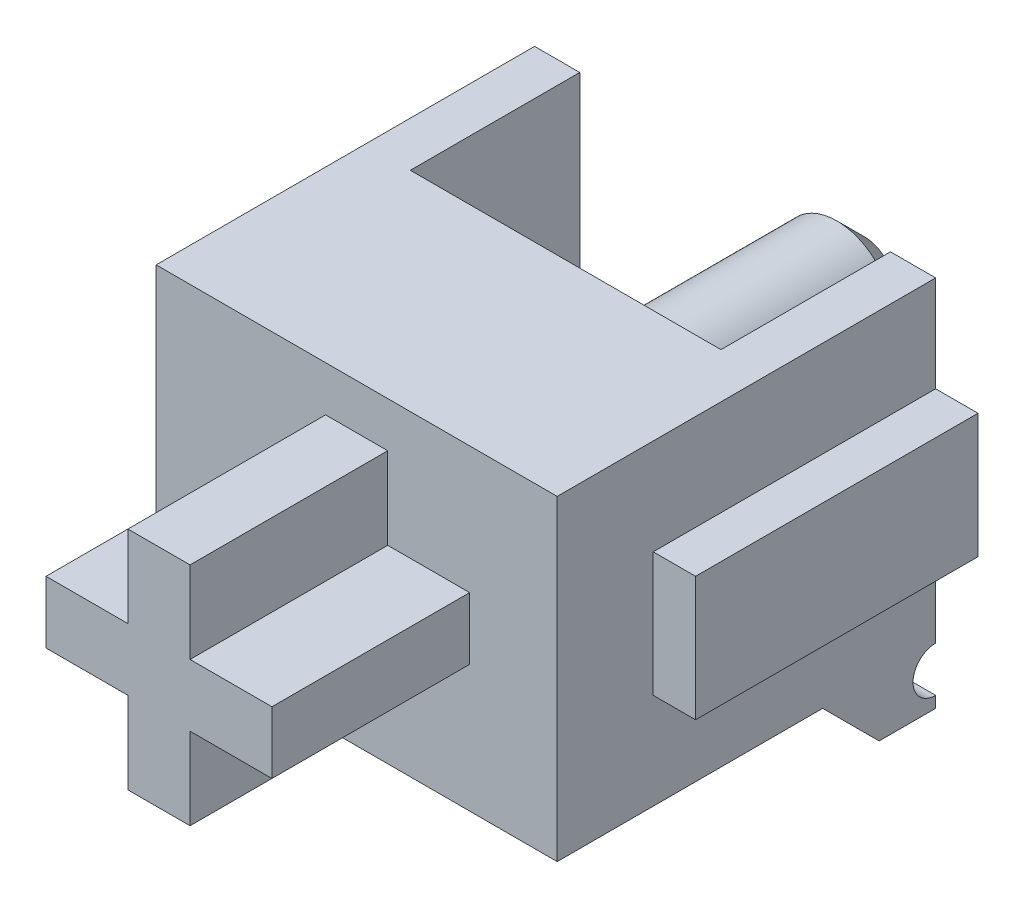
SolidWorks part; units mm, degrees
ref_plane "Front Plane" through (0, 0, 0) normal (0, 0, 1) x (1, 0, 0)
ref_plane "Top Plane" through (0, 0, 0) normal (0, 1, 0) x (1, 0, 0)
ref_plane "Right Plane" through (0, 0, 0) normal (1, 0, 0) x (0, 0, -1)
sketch "Sketch1" plane through (0, 0, 0) normal (0, 0, 1) x (1, 0, 0)
  line L1 (-3.55, 2.8) -> (3.55, 2.8)
  line L2 (-3.55, 2.8) -> (-3.55, -2.8)
  line L3 (-3.55, -2.8) -> (3.55, -2.8)
  line L4 (3.55, 2.8) -> (3.55, -2.8)
  line L5 (-3.55, 2.8) -> (3.55, -2.8) construction
  line L6 (-3.55, -2.8) -> (3.55, 2.8) construction
  point P0 (0, 0)
  dimension "D1" = 7.1
  dimension "D2" = 5.6
extrude "Boss-Extrude1" add sketch "Sketch1" along normal mid plane 6.7
sketch "Sketch2" plane through (0, 0, 3.35) normal (0, 0, 1) x (1, 0, 0)
  line L1 (-2, 2) -> (2, 2)
  line L2 (-2, 2) -> (-2, -2)
  line L3 (-2, -2) -> (2, -2)
  line L4 (2, 2) -> (2, -2)
  line L5 (-2, 2) -> (2, -2) construction
  line L6 (-2, -2) -> (2, 2) construction
  point P0 (0, 0)
  dimension "D1" = 4
extrude "Boss-Extrude2" add sketch "Sketch2" along normal blind 3.5
sketch "Sketch3" plane through (0, 0, 6.85) normal (0, 0, 1) x (1, 0, 0)
  line L1 (-2, 2) -> (-0.55, 2)
  line L2 (-2, 2) -> (-2, 0.55)
  line L3 (-2, 0.55) -> (-0.55, 0.55)
  line L4 (-0.55, 2) -> (-0.55, 0.55)
  dimension "D1" = 0.55
  dimension "D2" = 0.55
extrude "Cut-Extrude1" cut sketch "Sketch3" against normal blind 3.5
mirror "Mirror1" about plane through (0, 0, 0) normal (1, 0, 0) of "Cut-Extrude1"
mirror "Mirror2" about plane through (0, 0, 0) normal (0, 1, 0) of "Mirror1", "Cut-Extrude1"
sketch "Sketch4" plane through (-3.55, 0, 0) normal (-1, 0, 0) x (0, 0, 1)
  line L0 (-3.35, 2.8) -> (-3.35, -2.8) construction
  line L1 (-3.35, 1.1) -> (1.65, 1.1)
  line L2 (-3.35, 1.1) -> (-3.35, -1.1)
  line L3 (-3.35, -1.1) -> (1.65, -1.1)
  line L4 (1.65, 1.1) -> (1.65, -1.1)
  point P6 (1.65, 0)
  dimension "D1" = 5
  dimension "D2" = 2.2
extrude "Boss-Extrude3" add sketch "Sketch4" along normal blind 0.75
mirror "Mirror3" about plane through (0, 0, 0) normal (1, 0, 0) of "Boss-Extrude3"
sketch "Sketch5" plane through (0, 0, -3.35) normal (0, 0, -1) x (-1, 0, 0)
  line L0 (-3.55, 2.8) -> (3.55, 2.8) construction
  line L1 (-2.75, 2.8) -> (2.75, 2.8)
  line L2 (-2.75, 2.8) -> (-2.75, -2.8)
  line L3 (-2.75, -2.8) -> (2.75, -2.8)
  line L4 (2.75, 2.8) -> (2.75, -2.8)
  line L5 (3.55, -2.8) -> (-3.55, -2.8) construction
  line L6 (3.55, -1.1) -> (3.55, -2.8) construction
  line L7 (-3.55, -2.8) -> (-3.55, -1.1) construction
  dimension "D1" = 0.8
  dimension "D2" = 0.8
extrude "Cut-Extrude2" cut sketch "Sketch5" against normal blind 3
sketch "Sketch6" plane through (0, 0, -0.35) normal (0, 0, -1) x (-1, 0, 0)
  circle A0 centre (0, 0) radius 2.4
  dimension "D1" = 4.8
extrude "Cut-Extrude3" cut sketch "Sketch6" against normal blind 2
sketch "Sketch7" plane through (0, 0, 1.65) normal (0, 0, -1) x (-1, 0, 0)
  circle A0 centre (0, 0) radius 1
  dimension "D1" = 2
extrude "Boss-Extrude4" add sketch "Sketch7" along normal blind 7.3
chamfer "Chamfer1" distance 0.5 angle 45 1 edges at (-1, 0, -5.65)
sketch "Sketch8" plane through (3.55, 0, 0) normal (1, 0, 0) x (0, 0, -1)
  line L0 (1.35, -2.8) -> (2.35, -3.8)
  line L1 (-3.35, -2.8) -> (3.35, -2.8) construction
  line L2 (2.35, -3.8) -> (3.35, -3.8)
  line L3 (3.35, -3.8) -> (3.35, -2.8)
  line L4 (3.35, -2.8) -> (1.35, -2.8)
  dimension "D1" = 1
  dimension "D2" = 2
  dimension "D3" = 1
extrude "Boss-Extrude5" add sketch "Sketch8" against normal blind 0.8
sketch "Sketch9" plane through (3.55, 0, 0) normal (1, 0, 0) x (0, 0, -1)
  line L0 (3.35, -3.8) -> (3.35, -1.1) construction
  line L1 (2.35, -3.8) -> (3.35, -3.8) construction
  circle A0 centre (3.35, -3.2) radius 0.4
  dimension "D1" = 0.8
  dimension "D2" = 0.6
extrude "Cut-Extrude4" cut sketch "Sketch9" against normal blind 0.8
mirror "Mirror4" about plane through (0, 0, 0) normal (1, 0, 0) of "Cut-Extrude4", "Boss-Extrude5"
